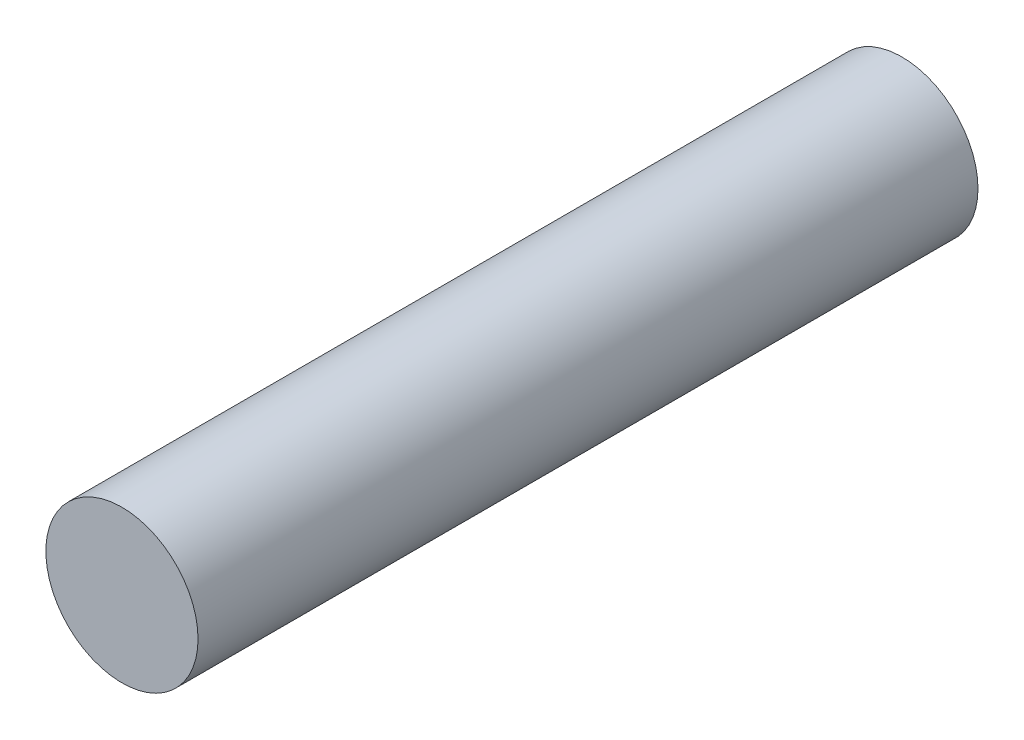
SolidWorks part; units mm, degrees
ref_plane "Front Plane" through (0, 0, 0) normal (0, 0, 1) x (1, 0, 0)
ref_plane "Top Plane" through (0, 0, 0) normal (0, 1, 0) x (1, 0, 0)
ref_plane "Right Plane" through (0, 0, 0) normal (1, 0, 0) x (0, 0, -1)
sketch "Sketch1" plane through (0, 0, 0) normal (0, 0, 1) x (1, 0, 0)
  circle A0 centre (0, 0) radius 4
  dimension "D1" = 8
extrude "Boss-Extrude1" add sketch "Sketch1" along normal blind 41
